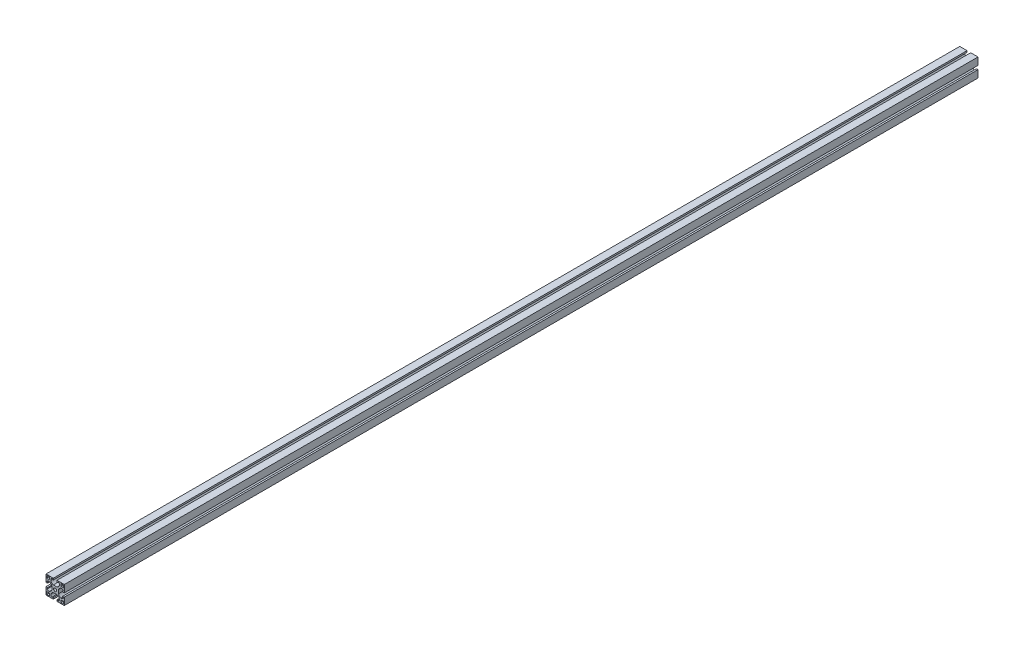
SolidWorks part; units mm, degrees
ref_plane "Plan de face" through (0, 0, 0) normal (0, 0, 1) x (1, 0, 0)
ref_plane "Plan de dessus" through (0, 0, 0) normal (0, 1, 0) x (1, 0, 0)
ref_plane "Plan de droite" through (0, 0, 0) normal (1, 0, 0) x (0, 0, -1)
sketch "Croquis1" plane through (0, 0, 0) normal (0, 0, 1) x (1, 0, 0)
  line L0 (16, 0) -> (16, 3.527)
  line L1 (0, 0) -> (16, 0)
  line L2 (0, 0) -> (0, 16)
  line L5 (16, 12.8) -> (20, 12.8)
  line L6 (16, 3.527) -> (13.842, 3.527)
  line L7 (13.842, 3.527) -> (13.842, 1.7641)
  line L8 (20, 20) -> (20, 12.8) construction
  line L9 (1.5646, 1.7635) -> (7.2656, 1.7635)
  line L10 (1.5646, 1.7635) -> (1.5646, 7.4332)
  line L11 (1.5646, 7.4332) -> (7.2656, 7.4332)
  line L12 (7.2656, 1.7635) -> (7.2656, 7.4332)
  line L13 (20, 20) -> (12.8, 20) construction
  line L14 (20, 20) -> (0, 0) construction
  line L15 (12.8, 16) -> (12.8, 20)
  line L16 (0, 16) -> (3.527, 16)
  line L17 (3.527, 13.842) -> (1.7641, 13.842)
  line L18 (3.527, 16) -> (3.527, 13.842)
  line L19 (20, 20) -> (12.8, 20) construction
  line L20 (12.8, 24) -> (12.8, 20)
  line L21 (16, 27.2) -> (20, 27.2)
  line L22 (3.527, 24) -> (3.527, 26.158)
  line L23 (3.527, 26.158) -> (1.7641, 26.158)
  line L24 (0, 24) -> (3.527, 24)
  line L25 (1.7635, 32.7344) -> (7.4332, 32.7344)
  line L26 (7.4332, 38.4354) -> (7.4332, 32.7344)
  line L27 (1.7635, 38.4354) -> (7.4332, 38.4354)
  line L28 (1.7635, 38.4354) -> (1.7635, 32.7344)
  line L29 (13.842, 36.473) -> (13.842, 38.2359)
  line L30 (16, 36.473) -> (13.842, 36.473)
  line L31 (16, 40) -> (16, 36.473)
  line L32 (0, 40) -> (0, 24)
  line L33 (0, 40) -> (16, 40)
  line L34 (20, 20) -> (20, 27.2) construction
  line L35 (24, 27.2) -> (20, 27.2)
  line L36 (27.2, 24) -> (27.2, 20)
  line L37 (24, 36.473) -> (26.158, 36.473)
  line L38 (26.158, 36.473) -> (26.158, 38.2359)
  line L39 (24, 40) -> (24, 36.473)
  line L40 (32.7344, 38.2365) -> (32.7344, 32.5668)
  line L41 (38.4354, 32.5668) -> (32.7344, 32.5668)
  line L42 (38.4354, 38.2365) -> (38.4354, 32.5668)
  line L43 (38.4354, 38.2365) -> (32.7344, 38.2365)
  line L44 (36.473, 26.158) -> (38.2359, 26.158)
  line L45 (36.473, 24) -> (36.473, 26.158)
  line L46 (40, 24) -> (36.473, 24)
  line L47 (40, 40) -> (24, 40)
  line L48 (40, 40) -> (40, 24)
  line L49 (20, 20) -> (27.2, 20) construction
  line L50 (27.2, 16) -> (27.2, 20)
  line L51 (24, 12.8) -> (20, 12.8)
  line L52 (36.473, 16) -> (36.473, 13.842)
  line L53 (36.473, 13.842) -> (38.2359, 13.842)
  line L54 (40, 16) -> (36.473, 16)
  line L55 (38.2365, 7.2656) -> (32.5668, 7.2656)
  line L56 (32.5668, 1.5646) -> (32.5668, 7.2656)
  line L57 (38.2365, 1.5646) -> (32.5668, 1.5646)
  line L58 (38.2365, 1.5646) -> (38.2365, 7.2656)
  line L59 (26.158, 3.527) -> (26.158, 1.7641)
  line L60 (24, 3.527) -> (26.158, 3.527)
  line L61 (24, 0) -> (24, 3.527)
  line L62 (40, 0) -> (40, 16)
  line L63 (40, 0) -> (24, 0)
  arc A0 (16.6, 20) -> (20, 16.6) centre (20, 20) ccw
  arc A1 (13.842, 1.7641) -> (10.5893, 7.4332) centre (14.961, 6.1738) cw
  arc A2 (10.5893, 7.4332) -> (16, 12.8) centre (19.9368, 3.42) cw
  arc A3 (1.7641, 13.842) -> (7.4332, 10.5893) centre (6.1738, 14.961) ccw
  arc A4 (7.4332, 10.5893) -> (12.8, 16) centre (3.42, 19.9368) ccw
  arc A5 (20, 23.4) -> (16.6, 20) centre (20, 20) ccw
  arc A6 (10.5893, 32.5668) -> (16, 27.2) centre (19.9368, 36.58) ccw
  arc A7 (7.4332, 29.4107) -> (12.8, 24) centre (3.42, 20.0632) cw
  arc A8 (1.7641, 26.158) -> (7.4332, 29.4107) centre (6.1738, 25.039) cw
  arc A9 (13.842, 38.2359) -> (10.5893, 32.5668) centre (14.961, 33.8262) ccw
  arc A10 (23.4, 20) -> (20, 23.4) centre (20, 20) ccw
  arc A11 (32.5668, 29.4107) -> (27.2, 24) centre (36.58, 20.0632) ccw
  arc A12 (29.4107, 32.5668) -> (24, 27.2) centre (20.0632, 36.58) cw
  arc A13 (26.158, 38.2359) -> (29.4107, 32.5668) centre (25.039, 33.8262) cw
  arc A14 (38.2359, 26.158) -> (32.5668, 29.4107) centre (33.8262, 25.039) ccw
  arc A15 (20, 16.6) -> (23.4, 20) centre (20, 20) ccw
  arc A16 (29.4107, 7.4332) -> (24, 12.8) centre (20.0632, 3.42) ccw
  arc A17 (32.5668, 10.5893) -> (27.2, 16) centre (36.58, 19.9368) cw
  arc A18 (38.2359, 13.842) -> (32.5668, 10.5893) centre (33.8262, 14.961) cw
  arc A19 (26.158, 1.7641) -> (29.4107, 7.4332) centre (25.039, 6.1738) ccw
  point P59 (20, 20)
  point P76 (22.5, 22.5)
  point P115 (20, 20)
  dimension "D2" = 6.8
  dimension "D4" = 12.8
  dimension "D6" = 4
extrude "Saliente-Extruir1" add sketch "Croquis1" along normal blind 2000
